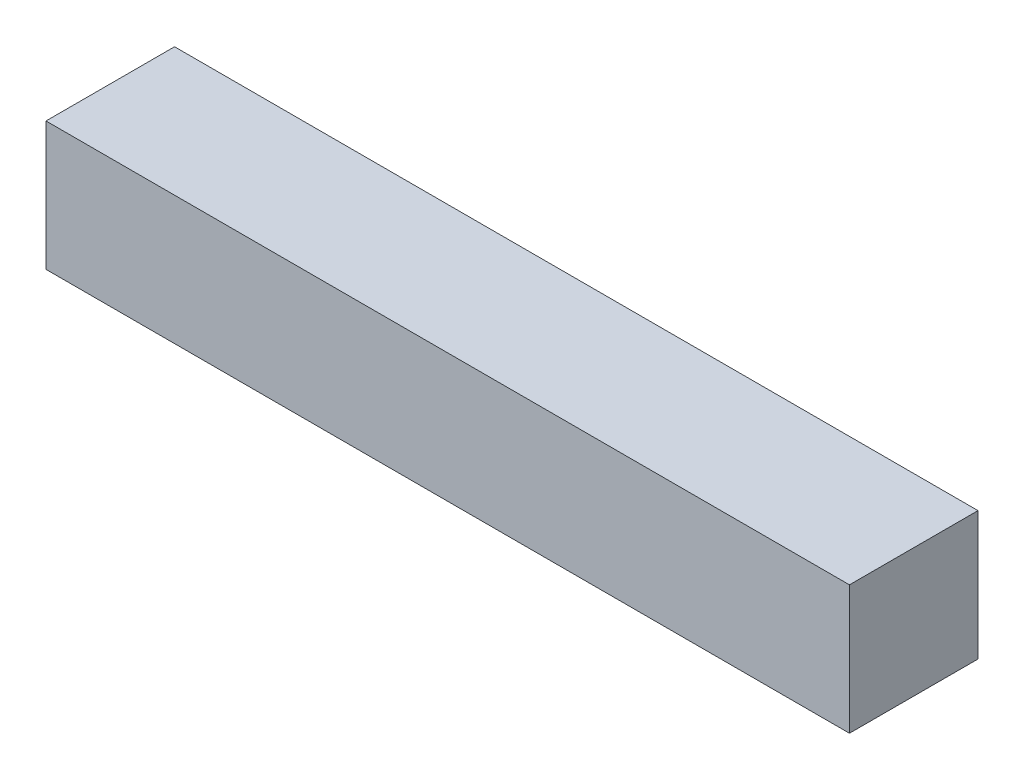
SolidWorks part; units mm, degrees
ref_plane "Front Plane" through (0, 0, 0) normal (0, 0, 1) x (1, 0, 0)
ref_plane "Top Plane" through (0, 0, 0) normal (0, 1, 0) x (1, 0, 0)
ref_plane "Right Plane" through (0, 0, 0) normal (1, 0, 0) x (0, 0, -1)
sketch "Sketch1" plane through (0, 0, 0) normal (1, 0, 0) x (0, 0, -1)
  line L1 (-20, 20) -> (20, 20)
  line L2 (-20, 20) -> (-20, -20)
  line L3 (-20, -20) -> (20, -20)
  line L4 (20, 20) -> (20, -20)
  dimension "D1" = 40
  dimension "D2" = 40
extrude "Boss-Extrude1" add sketch "Sketch1" along normal blind 250
